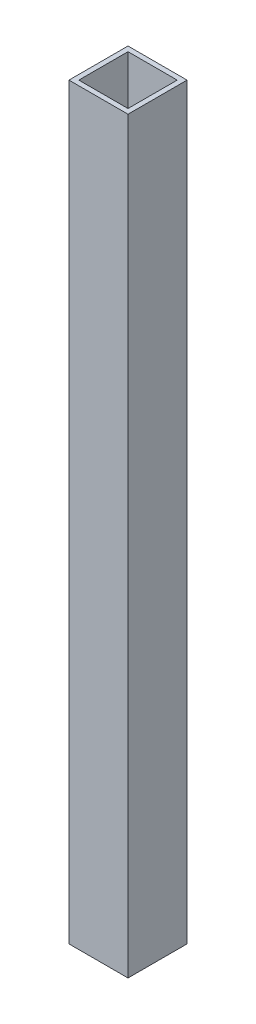
SolidWorks part; units mm, degrees
ref_plane "Front" through (0, 0, 0) normal (0, 0, 1) x (1, 0, 0)
ref_plane "Top" through (0, 0, 0) normal (0, 1, 0) x (1, 0, 0)
ref_plane "Right" through (0, 0, 0) normal (1, 0, 0) x (0, 0, -1)
sketch "Sketch1" plane through (0, 0, 0) normal (0, 1, 0) x (1, 0, 0)
  line L1 (0, 0) -> (19.05, 0)
  line L2 (0, 0) -> (0, 19.05)
  line L3 (0, 19.05) -> (19.05, 19.05)
  line L4 (19.05, 0) -> (19.05, 19.05)
  line L5 (0, 0) -> (19.05, 19.05) construction
  line L6 (0, 19.05) -> (19.05, 0) construction
  line L7 (1.5875, 1.5875) -> (17.4625, 1.5875)
  line L8 (1.5875, 1.5875) -> (1.5875, 17.4625)
  line L9 (1.5875, 17.4625) -> (17.4625, 17.4625)
  line L10 (17.4625, 1.5875) -> (17.4625, 17.4625)
  line L11 (1.5875, 1.5875) -> (17.4625, 17.4625) construction
  line L12 (1.5875, 17.4625) -> (17.4625, 1.5875) construction
  point P4 (9.525, 9.525)
  point P5 (9.525, 9.525)
  dimension "D1" = 1.5875
  dimension "D2" = 1.5875
  dimension "D3" = 19.05
extrude "Boss-Extrude1" add sketch "Sketch1" along normal blind 241.3
